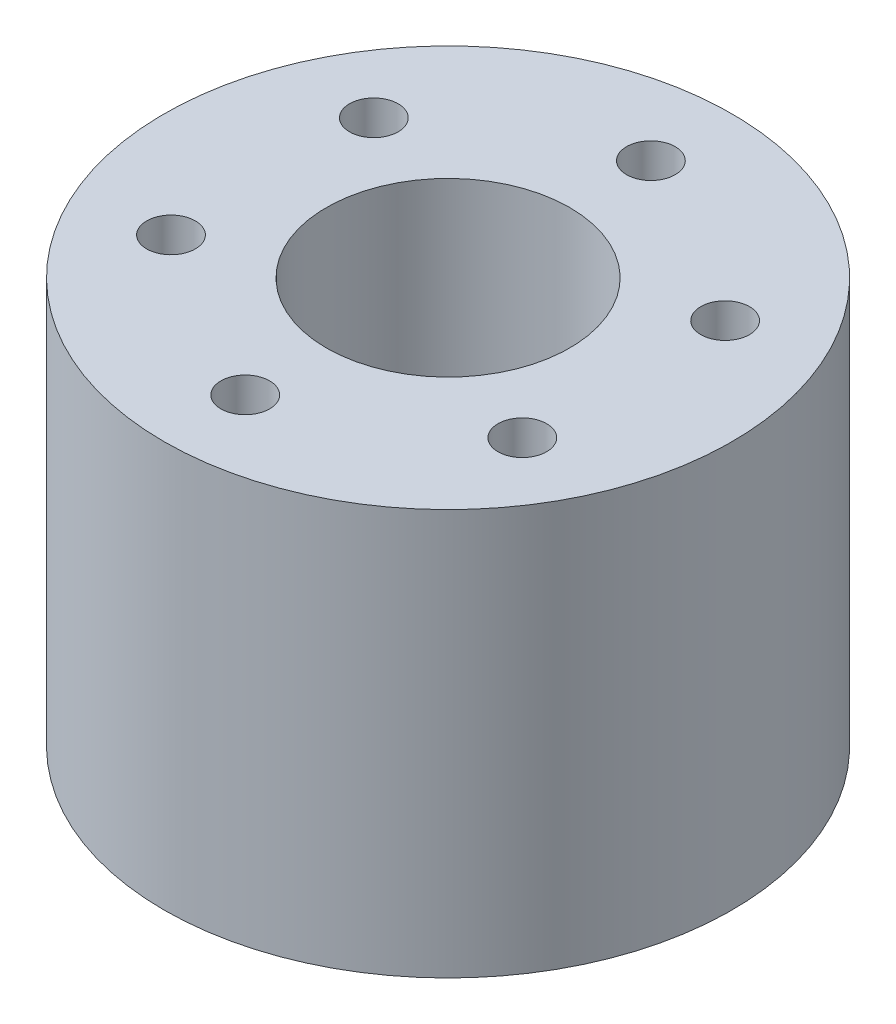
SolidWorks part; units mm, degrees
material "3.3547 (EN-AW 5083)"
ref_plane "Front Plane" through (0, 0, 0) normal (0, 0, 1) x (1, 0, 0)
ref_plane "Top Plane" through (0, 0, 0) normal (0, 1, 0) x (1, 0, 0)
ref_plane "Right Plane" through (0, 0, 0) normal (1, 0, 0) x (0, 0, -1)
sketch "Sketch1" plane through (0, 0, 0) normal (0, 1, 0) x (1, 0, 0)
  line L0 (0, -44.7868) -> (0, 44.7868) construction
  circle A0 centre (0, 0) radius 17.5
  circle A1 centre (0, 12.5) radius 1.5
  circle A2 centre (10.8253, 6.25) radius 1.5
  circle A3 centre (10.8253, -6.25) radius 1.5
  circle A4 centre (0, -12.5) radius 1.5
  circle A5 centre (-10.8253, -6.25) radius 1.5
  circle A6 centre (-10.8253, 6.25) radius 1.5
  circle A7 centre (0, 0) radius 7.5
  point P8 (0, 0)
  point P21 (0, 0)
  dimension "D1" = 35
  dimension "D2" = 6
  dimension "D3" = 3
  dimension "D5" = 15
  dimension "D4" = 12.5
extrude "Boss-Extrude1" add sketch "Sketch1" along normal blind 25
